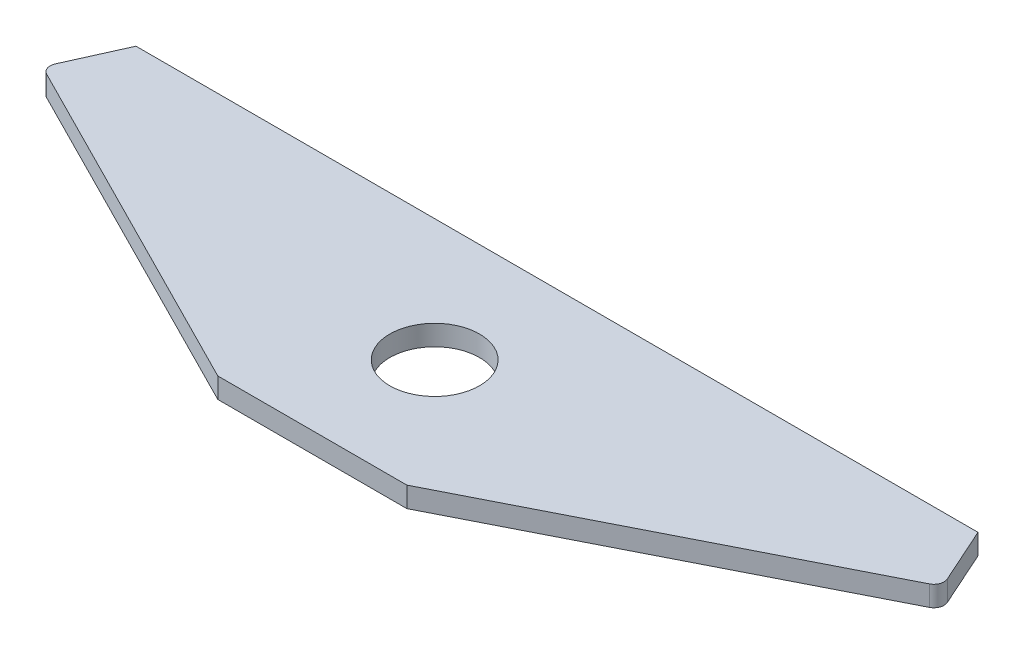
SolidWorks part; units mm, degrees
material "ASTM A36 Steel"
ref_plane "Front Plane" through (0, 0, 0) normal (0, 0, 1) x (1, 0, 0)
ref_plane "Top Plane" through (0, 0, 0) normal (0, 1, 0) x (1, 0, 0)
ref_plane "Right Plane" through (0, 0, 0) normal (1, 0, 0) x (0, 0, -1)
sketch "Sketch1" plane through (0, 0, 0) normal (0, 1, 0) x (1, 0, 0)
  line L0 (224.059, 44.1091) -> (-188.883, 44.1091)
  line L1 (17.588, -75.8909) -> (-28.764, -75.8909)
  line L2 (224.059, 44.1091) -> (236.3317, 16.7942)
  line L3 (-188.883, 44.1091) -> (-201.1556, 16.7942)
  line L4 (234.0306, 10.2848) -> (63.9401, -75.8909)
  line L5 (-198.8546, 10.2848) -> (-28.764, -75.8909)
  line L6 (17.588, -75.8909) -> (63.9401, -75.8909)
  arc A0 (234.0306, 10.2848) -> (236.3317, 16.7942) centre (231.7709, 14.7451) ccw
  arc A1 (-201.1556, 16.7942) -> (-198.8546, 10.2848) centre (-196.5948, 14.7451) ccw
extrude "Boss-Extrude1" add sketch "Sketch1" along normal blind 10
sketch "Sketch2" plane through (0, 10, 0) normal (0, 1, 0) x (1, 0, 0)
  line L0 (224.059, 44.1091) -> (-188.883, 44.1091) construction
  circle A0 centre (17.588, -15.8909) radius 22
  dimension "D1" = 44
  dimension "D2" = 60
extrude "Cut-Extrude1" cut sketch "Sketch2" against normal blind 10
